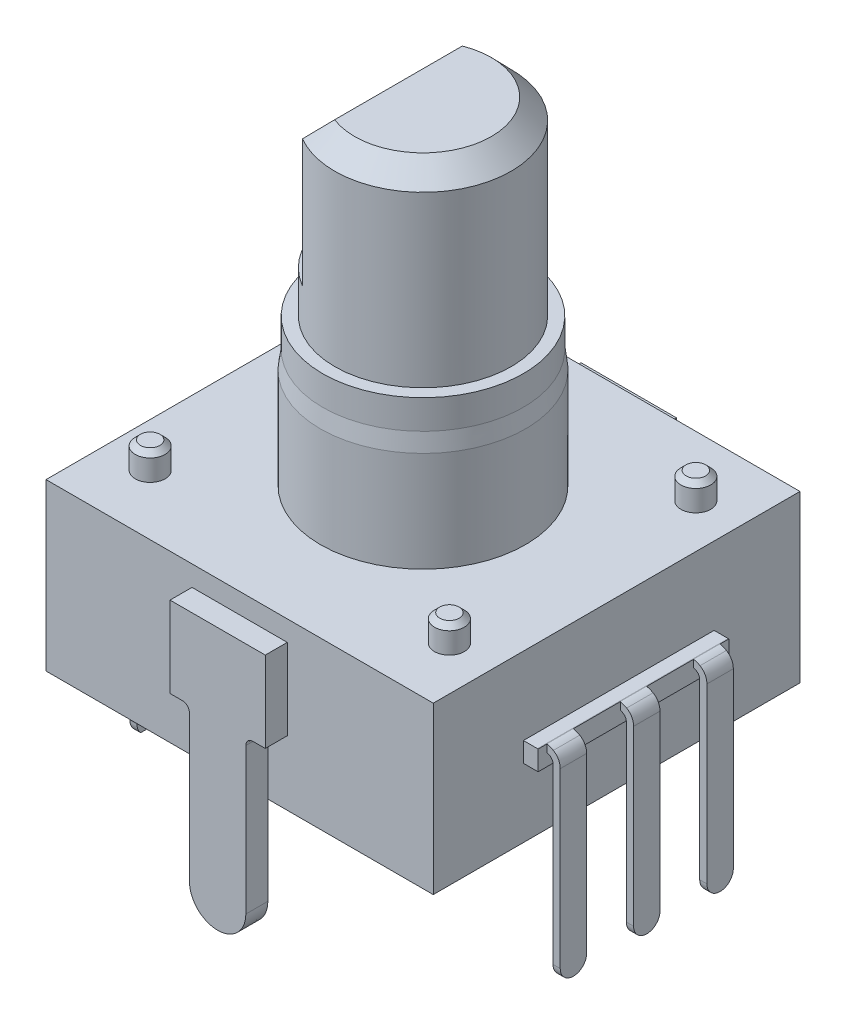
SolidWorks part; units mm, degrees
ref_plane "Front Plane" through (0, 0, 0) normal (0, 0, 1) x (1, 0, 0)
ref_plane "Top Plane" through (0, 0, 0) normal (0, 1, 0) x (1, 0, 0)
ref_plane "Right Plane" through (0, 0, 0) normal (1, 0, 0) x (0, 0, -1)
sketch "Sketch1" plane through (0, 0, 0) normal (0, 0, 1) x (1, 0, 0)
  line L0 (0.9604, -8.6703) -> (0.9604, -3.696)
  line L1 (1.2053, -3.4512) -> (1.6232, -3.4512)
  line L2 (1.6232, -3.4512) -> (1.6232, -2.2855)
  line L3 (1.8681, -2.0407) -> (2.9665, -2.0407)
  line L4 (3.2114, -2.2855) -> (3.2114, -5.6119)
  line L5 (3.2114, -5.6119) -> (4.3519, -5.6119)
  line L6 (4.3519, -5.6119) -> (4.3519, -3.456)
  line L7 (4.5967, -3.211) -> (5.1321, -3.211)
  line L8 (5.1321, -3.211) -> (5.1321, 0)
  line L9 (5.1321, 0) -> (-5.1321, 0)
  line L10 (-5.1321, 0) -> (-5.1321, -3.211)
  line L11 (-5.1321, -3.211) -> (-4.5367, -3.211)
  line L12 (-4.2918, -3.456) -> (-4.2918, -5.6119)
  line L13 (-4.2918, -5.6119) -> (-3.2113, -5.6119)
  line L14 (-3.2113, -5.6119) -> (-3.2113, -2.2855)
  line L15 (-2.9664, -2.0407) -> (-1.868, -2.0407)
  line L16 (-1.623, -2.2855) -> (-1.623, -3.4512)
  line L17 (-1.623, -3.4512) -> (-1.2053, -3.4512)
  line L18 (-0.9604, -3.696) -> (-0.9604, -8.6703)
  line L19 (-4.2918, -5.2036) -> (-4.8159, -5.2036)
  line L20 (-4.8159, -5.2036) -> (-4.8159, -3.211)
  line L21 (4.3519, -5.2036) -> (4.8761, -5.2036)
  line L22 (4.8761, -5.2036) -> (4.8761, -3.211)
  line L23 (-6.5709, -0.3469) -> (-5.132, -0.3469)
  line L24 (-5.132, -0.3469) -> (-5.132, -0.0001)
  line L25 (-5.132, -0.0001) -> (-6.5709, -0.0001)
  line L26 (-6.5709, -0.0001) -> (-6.5709, -0.3469)
  line L27 (-4.8158, -5.0402) -> (-6.5506, -5.0402)
  line L28 (-6.5506, -5.0402) -> (-6.5506, -0.5713)
  line L29 (-6.5506, -0.5713) -> (-5.132, -0.5713)
  line L30 (-6.2444, -5.0402) -> (-6.2444, -5.6524)
  line L31 (-6.2444, -5.6524) -> (-4.7341, -5.6524)
  line L32 (-4.7341, -5.6524) -> (-4.7341, -5.2036)
  line L33 (-5.8974, -0.5713) -> (-5.8974, -0.3468)
  line L34 (-6.4484, -0.5713) -> (-6.4484, -0.3468)
  line L35 (6.6731, -0.3468) -> (5.1321, -0.3468)
  line L36 (5.1321, -0.3468) -> (5.1321, 0)
  line L37 (5.1321, 0) -> (6.6731, 0)
  line L38 (6.6731, 0) -> (6.6731, -0.3468)
  line L39 (5.8976, -0.5713) -> (5.8976, -0.3468)
  line L40 (6.4487, -0.5713) -> (6.4487, -0.3468)
  line L41 (-6.0595, -0.5713) -> (-6.0595, -5.0402)
  line L42 (4.8761, -5.0402) -> (6.6733, -5.0402)
  line L43 (6.6733, -5.0402) -> (6.6733, -0.5713)
  line L44 (6.6733, -0.5713) -> (5.1322, -0.5713)
  line L45 (6.1822, -0.5713) -> (6.1822, -5.0402)
  line L46 (-5.979, -5.6524) -> (-5.979, -5.0402)
  line L47 (-5.7749, -5.6524) -> (-5.7749, -5.0402)
  line L48 (6.123, -5.0402) -> (6.123, -5.6524)
  line L49 (6.123, -5.6524) -> (4.4902, -5.6524)
  line L50 (4.4902, -5.6524) -> (4.4902, -5.2036)
  line L51 (5.8575, -5.6524) -> (5.8575, -5.0402)
  line L52 (5.6534, -5.6524) -> (5.6534, -5.0402)
  line L53 (-3.2112, -5.2239) -> (-0.9603, -5.2239)
  line L54 (0.9605, -5.2239) -> (3.2114, -5.2239)
  line L55 (-1.623, -3.2241) -> (-3.2112, -3.2241)
  line L56 (-3.2112, -2.8161) -> (-1.623, -2.8161)
  line L57 (3.2114, -3.2241) -> (1.6232, -3.2241)
  line L58 (1.6232, -2.8161) -> (3.2114, -2.8161)
  line L59 (7.1438, -2.811) -> (6.6733, -2.811)
  line L60 (6.6733, -2.811) -> (6.6733, -2.5659)
  line L61 (6.6733, -2.5659) -> (7.1532, -2.5659)
  line L62 (7.1532, -2.5659) -> (7.169, -2.5671)
  line L63 (7.6279, -9.4224) -> (7.3829, -9.4224)
  line L64 (7.6276, -3.0711) -> (7.3829, -3.0711)
  line L65 (7.1742, -2.5671) -> (7.1742, -3.2394)
  line L66 (7.1742, -3.2394) -> (6.673, -3.2394)
  line L67 (-6.7103, -4.5472) -> (-6.5507, -4.5472)
  line L68 (-6.5507, -4.5472) -> (-6.5507, -4.792)
  line L69 (-6.5507, -4.792) -> (-6.7234, -4.792)
  line L70 (-6.7234, -4.792) -> (-6.7308, -4.7909)
  line L71 (-6.7308, -4.7909) -> (-6.7314, -4.7913)
  line L72 (-6.7997, -9.2849) -> (-7.0448, -9.2849)
  line L73 (-7.0448, -5.7967) -> (-7.1467, -5.8986)
  line L74 (-7.1467, -5.8986) -> (-7.1467, -8.5227)
  line L75 (-7.1467, -8.5227) -> (-7.0128, -8.6564)
  line L76 (0.9605, -6.6729) -> (-0.9603, -6.6729)
  line L77 (0.9605, -6.8973) -> (-0.9603, -6.8973)
  line L78 (0.9605, -7.4483) -> (-0.9603, -7.4483)
  line L79 (0.9605, -8.1829) -> (-0.9603, -8.1829)
  line L80 (5.1322, -0.6939) -> (-5.132, -0.6939)
  line L81 (4.5922, 0.6938) -> (5.6127, 0.6938)
  line L82 (5.6127, 0.6938) -> (5.6127, -0.0001)
  line L83 (5.6127, -0.0001) -> (4.5922, -0.0001)
  line L84 (4.5922, -0.0001) -> (4.5922, 0.6938)
  line L85 (4.7779, 0.8981) -> (5.4267, 0.8981)
  line L86 (5.4267, 0.8981) -> (5.6125, 0.6938)
  line L87 (5.6125, 0.6938) -> (4.592, 0.6938)
  line L88 (4.592, 0.6938) -> (4.7779, 0.8981)
  line L89 (-5.6249, 0.694) -> (-4.6044, 0.694)
  line L90 (-4.6044, 0.694) -> (-4.6044, 0)
  line L91 (-4.6044, 0) -> (-5.6249, 0)
  line L92 (-5.6249, 0) -> (-5.6249, 0.694)
  line L93 (-5.4391, 0.8981) -> (-4.7903, 0.8981)
  line L94 (-4.7903, 0.8981) -> (-4.6044, 0.6938)
  line L95 (-4.6044, 0.6938) -> (-5.6249, 0.6938)
  line L96 (-5.6249, 0.6938) -> (-5.4391, 0.8981)
  line L97 (3.4953, -0.0002) -> (-3.4842, -0.0002)
  line L98 (-3.4842, -0.0002) -> (-3.4842, 3.4179)
  line L99 (-3.4842, 3.4179) -> (3.4953, 3.4179)
  line L100 (3.4953, 3.4179) -> (3.4953, -0.0002)
  line L101 (3.4188, 4.0148) -> (-3.4076, 4.0148)
  line L102 (-3.4076, 4.0148) -> (-3.4076, 5.0096)
  line L103 (-3.4076, 5.0096) -> (3.4188, 5.0096)
  line L104 (3.4188, 5.0096) -> (3.4953, 3.4179)
  line L105 (3.4953, 3.4179) -> (3.4188, 4.0148)
  line L106 (-3.4842, 3.4179) -> (-3.4076, 4.0148)
  line L107 (-3.1015, 5.9432) -> (3.0056, 5.9432)
  line L108 (3.0056, 5.9432) -> (3.0056, 5.0096)
  line L109 (3.0056, 5.0096) -> (-3.1015, 5.0096)
  line L110 (-3.1015, 5.0096) -> (-3.1015, 5.9432)
  line L111 (-1.5096, 10.7793) -> (-1.5096, 6.4329)
  line L112 (-1.5096, 6.4329) -> (-2.9943, 6.4329)
  line L113 (-2.9943, 6.4329) -> (-2.9943, 5.9432)
  line L114 (-2.9943, 5.9432) -> (3.0056, 5.9432)
  line L115 (3.0056, 5.9432) -> (3.0056, 10.7793)
  line L116 (3.0056, 10.7793) -> (-1.5096, 10.7793)
  line L117 (-0.8362, 11.4681) -> (2.3321, 11.4681)
  line L118 (2.3321, 11.4681) -> (3.0056, 10.7793)
  line L119 (3.0056, 10.7793) -> (-1.5096, 10.7793)
  line L120 (-1.5096, 10.7793) -> (-0.8362, 11.4681)
  spline S0 degree 3 poles (-0.9604, -8.6703) (-0.9604, -9.2007) (-0.5303, -9.6305) (-0.0001, -9.6305) knots 0 0 0 0 1 1 1 1
  spline S1 degree 3 poles (-0.0001, -9.6305) (0.5304, -9.6305) (0.9604, -9.2007) (0.9604, -8.6703) knots 1 1 1 1 2 2 2 2
  spline S2 degree 3 poles (0.9604, -3.696) (0.9604, -3.5613) (1.0706, -3.4512) (1.2053, -3.4512) knots 3 3 3 3 4 4 4 4
  spline S3 degree 3 poles (1.6232, -2.2855) (1.6232, -2.1509) (1.7334, -2.0407) (1.8681, -2.0407) knots 6 6 6 6 7 7 7 7
  spline S4 degree 3 poles (2.9665, -2.0407) (3.1011, -2.0407) (3.2114, -2.1509) (3.2114, -2.2855) knots 8 8 8 8 9 9 9 9
  spline S5 degree 3 poles (4.3519, -3.456) (4.3519, -3.3212) (4.4621, -3.211) (4.5967, -3.211) knots 12 12 12 12 13 13 13 13
  spline S6 degree 3 poles (-4.5367, -3.211) (-4.402, -3.211) (-4.2918, -3.3212) (-4.2918, -3.456) knots 18 18 18 18 19 19 19 19
  spline S7 degree 3 poles (-3.2113, -2.2855) (-3.2113, -2.1509) (-3.101, -2.0407) (-2.9664, -2.0407) knots 22 22 22 22 23 23 23 23
  spline S8 degree 3 poles (-1.868, -2.0407) (-1.7332, -2.0407) (-1.623, -2.1509) (-1.623, -2.2855) knots 24 24 24 24 25 25 25 25
  spline S9 degree 3 poles (-1.2053, -3.4512) (-1.0706, -3.4512) (-0.9604, -3.5613) (-0.9604, -3.696) knots 27 27 27 27 28 28 28 28
  spline S10 degree 3 poles (7.3829, -9.4224) (7.3827, -9.4224) (7.3827, -3.4078) (7.3829, -3.0711) knots 0 0 0 0 1 1 1 1
  spline S11 degree 3 poles (7.3829, -3.0711) (7.3829, -2.8966) (7.2574, -2.8477) (7.1742, -2.8184) knots 1 1 1 1 2 2 2 2
  spline S12 degree 3 poles (7.1742, -2.8184) (7.1597, -2.8143) (7.1496, -2.8121) (7.1438, -2.811) knots 2 2 2 2 3 3 3 3
  spline S13 degree 3 poles (7.169, -2.5671) (7.1784, -2.5688) (7.2801, -2.5812) (7.3928, -2.6489) knots 7 7 7 7 8 8 8 8
  spline S14 degree 3 poles (7.3928, -2.6489) (7.505, -2.7135) (7.6302, -2.8568) (7.6276, -3.0711) knots 8 8 8 8 9 9 9 9
  spline S15 degree 3 poles (7.6276, -3.0711) (7.6276, -3.4076) (7.6276, -9.4224) (7.6279, -9.4224) knots 9 9 9 9 10 10 10 10
  spline S16 degree 3 poles (-7.0448, -9.2849) (-7.0448, -9.2847) (-7.0448, -5.1254) (-7.0448, -4.8849) knots 0 0 0 0 1 1 1 1
  spline S17 degree 3 poles (-7.0448, -4.8849) (-7.0474, -4.7576) (-6.9914, -4.6523) (-6.9154, -4.6021) knots 1 1 1 1 2 2 2 2
  spline S18 degree 3 poles (-6.9154, -4.6021) (-6.8412, -4.5511) (-6.7694, -4.547) (-6.7314, -4.5465) knots 2 2 2 2 3 3 3 3
  spline S19 degree 3 poles (-6.7314, -4.5465) (-6.7228, -4.5465) (-6.7158, -4.5469) (-6.7103, -4.5472) knots 3 3 3 3 4 4 4 4
  spline S20 degree 3 poles (-6.7314, -4.7913) (-6.7426, -4.7906) (-6.7661, -4.7952) (-6.775, -4.8023) knots 9 9 9 9 10 10 10 10
  spline S21 degree 3 poles (-6.775, -4.8023) (-6.7823, -4.8103) (-6.7973, -4.8132) (-6.7999, -4.8849) knots 10 10 10 10 11 11 11 11
  spline S22 degree 3 poles (-6.7999, -4.8849) (-6.7999, -5.1254) (-6.7999, -9.2805) (-6.7997, -9.2849) knots 11 11 11 11 12 12 12 12
sketch "Sketch2" plane through (0, 0, 0) normal (0, 0, 1) x (1, 0, 0)
  line L0 (0, 0) -> (0, -13.1499) construction
  line L1 (0, -13.5399) -> (0, 13.5399) construction
  line L2 (-0.8362, 11.4681) -> (2.3321, 11.4681) construction
  line L3 (2.3321, 11.4681) -> (3.0056, 10.7793) construction
  line L4 (3.0056, 5.9432) -> (3.0056, 10.7793) construction
  line L5 (0, 11.4681) -> (0, 0)
  line L7 (-3.4842, 3.4179) -> (3.4953, 3.4179) construction
  line L8 (3.4953, 3.4179) -> (3.4953, -0.0002) construction
  line L10 (0, 11.4681) -> (2.3321, 11.4681)
  line L11 (2.3321, 11.4681) -> (3.0056, 10.7793)
  line L12 (3.0056, 5.0096) -> (3.0056, 10.7793)
  line L14 (3.0056, 5.0096) -> (3.4188, 5.0096)
  line L15 (3.4188, 5.0096) -> (3.4188, 4.0148)
  line L16 (3.4953, 3.4179) -> (3.4953, 0)
  line L18 (3.4188, 4.0148) -> (3.4953, 3.4179)
  line L19 (-3.4076, 5.0096) -> (3.4188, 5.0096) construction
  line L20 (3.4953, 0) -> (0, 0)
revolve "Revolve10" add sketch "Sketch2" angle 360 about L0
sketch "Sketch3" plane through (0, 0, 0) normal (0, 0, 1) x (1, 0, 0)
  line L0 (-1.5096, 6.4329) -> (-2.9943, 6.4329) construction
  line L1 (-1.5096, 10.7793) -> (-1.5096, 6.4329) construction
  line L2 (-1.5096, 6.4329) -> (-3.0056, 6.4329)
  line L3 (-1.5096, 11.4681) -> (-1.5096, 6.4329)
  line L4 (-3.0056, 10.7793) -> (-3.0056, 5.0096) construction
  line L5 (2.3321, 11.4681) -> (-2.3321, 11.4681) construction
  line L6 (-3.0056, 11.4681) -> (-3.0056, 6.4329)
  line L7 (-1.5096, 11.4681) -> (-3.0056, 11.4681)
extrude "Cut-Extrude1" cut sketch "Sketch3" against normal up to next and the other way up to next
sketch "Sketch4" plane through (0, 0, 0) normal (0, -1, 0) x (1, 0, 0)
  line L1 (-6.6, -6.25) -> (6.6, -6.25)
  line L2 (-6.6, -6.25) -> (-6.6, 6.25)
  line L3 (-6.6, 6.25) -> (6.6, 6.25)
  line L4 (6.6, -6.25) -> (6.6, 6.25)
  line L5 (-6.6, -6.25) -> (6.6, 6.25) construction
  line L6 (-6.6, 6.25) -> (6.6, -6.25) construction
  point P0 (0, 0)
  dimension "D1" = 13.2
  dimension "D2" = 12.5
extrude "Boss-Extrude1" add sketch "Sketch4" along normal up to vertex (5.6524 mm away) up to point (-4.7341, -5.6524, 0)
sketch "Sketch5" plane through (0, 0, 0) normal (0, 0, 1) x (1, 0, 0)
  line L0 (-1.5096, 10.7793) -> (-0.8362, 11.4681) construction
  line L1 (-1.5096, 10.7793) -> (-0.8362, 11.4681)
  line L2 (-1.5096, 10.7793) -> (-1.5096, 11.4681)
  line L3 (-1.5096, 11.4681) -> (-0.8362, 11.4681)
extrude "Cut-Extrude2" cut sketch "Sketch5" against normal up to next and the other way up to next
sketch "Sketch6" plane through (0, 0, 0) normal (0, 1, 0) x (1, 0, 0)
  line L0 (0, 0) -> (0, 8.5463) construction
  line L1 (0, -6.875) -> (0, 6.875) construction
  line L2 (0, 0) -> (11.4741, 0) construction
  circle A0 centre (-5.1, 4.2) radius 0.508
  circle A1 centre (5.1, 4.2) radius 0.508
  circle A2 centre (5.1, -4.2) radius 0.508
  circle A3 centre (-5.1, -4.2) radius 0.508
  dimension "D1" = 8.4
  dimension "D2" = 10.2
  dimension "D3" = 1.016
extrude "Boss-Extrude2" add sketch "Sketch6" along normal up to vertex (0.8981 mm away) up to point (-4.7903, 0.8981, 0)
chamfer "Chamfer1" distance 0.1778 angle 45 4 edges at (5.1, 0.8981, -3.692) (5.1, 0.8981, 4.708) (-5.1, 0.8981, -3.692) (-5.1, 0.8981, 4.708)
sketch "Sketch7" plane through (0, 0, 6.25) normal (0, 0, 1) x (1, 0, 0)
  line L0 (-1.623, -2.2855) -> (-1.623, -3.4512) construction
  line L1 (-1.623, -3.4512) -> (-1.2053, -3.4512) construction
  line L2 (-0.9604, -3.696) -> (-0.9604, -8.6703) construction
  line L3 (0.9604, -8.6703) -> (0.9604, -3.696) construction
  line L4 (1.2053, -3.4512) -> (1.6232, -3.4512) construction
  line L5 (1.6232, -3.4512) -> (1.6232, -2.2855) construction
  line L6 (5.1322, -0.6939) -> (-5.132, -0.6939) construction
  line L7 (-1.623, -0.6939) -> (-1.623, -3.4512)
  line L8 (-1.623, -3.4512) -> (-1.2053, -3.4512)
  line L9 (-0.9604, -3.696) -> (-0.9604, -8.6703)
  line L10 (0.9604, -8.6703) -> (0.9604, -3.696)
  line L11 (1.2053, -3.4512) -> (1.6232, -3.4512)
  line L12 (1.6232, -3.4512) -> (1.6232, -0.6939)
  line L13 (1.6232, -0.6939) -> (-1.623, -0.6939)
  spline S0 degree 3 poles (1943.8592, -2286.133) (-2070.6571, 2174.6987) (2182.9501, -2067.0268) (-2288.9997, 1934.9357) knots -1.659555 -1.659555 -1.659555 -1.659555 56.657088 56.657088 56.657088 56.657088 only from (-1.2053, -3.4512) to (-0.9604, -3.696) construction
  spline S1 degree 3 poles (2377.6186, -1832.4346) (-2221.6581, 2023.1897) (2037.0941, -2225.5259) (-1829.3523, 2364.642) knots -18.097303 -18.097303 -18.097303 -18.097303 19.098909 19.098909 19.098909 19.098909 only from (-0.9604, -8.6703) to (-0.0001, -9.6305) construction
  spline S2 degree 3 poles (1827.1972, 2366.3822) (-2035.2287, -2227.2818) (2220.0923, 2024.9396) (-2376.3586, -1834.1534) knots -17.103608 -17.103608 -17.103608 -17.103608 20.102828 20.102828 20.102828 20.102828 only from (-0.0001, -9.6305) to (0.9604, -8.6703) construction
  spline S3 degree 3 poles (2289.0612, 1934.9907) (-2182.9667, -2067.0457) (2070.6329, 2174.6767) (-1943.799, -2286.0661) knots -25.657355 -25.657355 -25.657355 -25.657355 32.659263 32.659263 32.659263 32.659263 only from (0.9604, -3.696) to (1.2053, -3.4512) construction
  spline S4 degree 3 poles (-1.2053, -3.4512) (-1.0706, -3.4512) (-0.9604, -3.5613) (-0.9604, -3.696) knots 27 27 27 27 28 28 28 28
  spline S5 degree 3 poles (-0.9604, -8.6703) (-0.9604, -9.2007) (-0.5303, -9.6305) (-0.0001, -9.6305) knots 0 0 0 0 1 1 1 1
  spline S6 degree 3 poles (-0.0001, -9.6305) (0.5304, -9.6305) (0.9604, -9.2007) (0.9604, -8.6703) knots 1 1 1 1 2 2 2 2
  spline S7 degree 3 poles (0.9604, -3.696) (0.9604, -3.5613) (1.0706, -3.4512) (1.2053, -3.4512) knots 3 3 3 3 4 4 4 4
extrude "Boss-Extrude3" add sketch "Sketch7" along normal offset from surface (0.75 mm away) 7 up to plane "Front Plane"
sketch "Sketch8" plane through (0, 0, -6.25) normal (0, 0, -1) x (-1, 0, 0)
  line L7 (1.623, -0.6939) -> (1.623, -3.4512) construction
  line L8 (-1.6232, -0.6939) -> (1.623, -0.6939) construction
  line L9 (-1.6232, -3.4512) -> (-1.6232, -0.6939) construction
  line L10 (-1.2053, -3.4512) -> (-1.6232, -3.4512) construction
  line L11 (-0.9604, -8.6703) -> (-0.9604, -3.696) construction
  line L12 (1.623, -3.4512) -> (1.2053, -3.4512) construction
  line L13 (0.9604, -3.696) -> (0.9604, -8.6703) construction
  line L14 (1.623, -0.6939) -> (1.623, -3.4512)
  line L15 (-1.6232, -0.6939) -> (1.623, -0.6939)
  line L16 (-1.6232, -3.4512) -> (-1.6232, -0.6939)
  line L17 (-1.2053, -3.4512) -> (-1.6232, -3.4512)
  line L18 (-0.9604, -8.6703) -> (-0.9604, -3.696)
  line L19 (1.623, -3.4512) -> (1.2053, -3.4512)
  line L20 (0.9604, -3.696) -> (0.9604, -8.6703)
  spline S4 degree 3 poles (-2289.0612, 1934.9907) (2182.9667, -2067.0457) (-2070.6329, 2174.6767) (1943.799, -2286.0661) knots -25.657355 -25.657355 -25.657355 -25.657355 32.659263 32.659263 32.659263 32.659263 only from (-0.9604, -3.696) to (-1.2053, -3.4512) construction
  spline S5 degree 3 poles (-1943.8592, -2286.133) (2070.6571, 2174.6987) (-2182.9501, -2067.0268) (2288.9997, 1934.9357) knots -1.659555 -1.659555 -1.659555 -1.659555 56.657088 56.657088 56.657088 56.657088 only from (1.2053, -3.4512) to (0.9604, -3.696) construction
  spline S6 degree 3 poles (-1827.1972, 2366.3822) (2035.2287, -2227.2818) (-2220.0923, 2024.9396) (2376.3586, -1834.1534) knots -17.103608 -17.103608 -17.103608 -17.103608 20.102828 20.102828 20.102828 20.102828 only from (0.0001, -9.6305) to (-0.9604, -8.6703) construction
  spline S7 degree 3 poles (-2377.6186, -1832.4346) (2221.6581, 2023.1897) (-2037.0941, -2225.5259) (1829.3523, 2364.642) knots -18.097303 -18.097303 -18.097303 -18.097303 19.098909 19.098909 19.098909 19.098909 only from (0.9604, -8.6703) to (0.0001, -9.6305) construction
  spline S8 degree 3 poles (-0.9604, -3.696) (-0.9604, -3.5613) (-1.0706, -3.4512) (-1.2053, -3.4512) knots 3 3 3 3 4 4 4 4
  spline S9 degree 3 poles (1.2053, -3.4512) (1.0706, -3.4512) (0.9604, -3.5613) (0.9604, -3.696) knots 27 27 27 27 28 28 28 28
  spline S10 degree 3 poles (0.0001, -9.6305) (-0.5304, -9.6305) (-0.9604, -9.2007) (-0.9604, -8.6703) knots 1 1 1 1 2 2 2 2
  spline S11 degree 3 poles (0.9604, -8.6703) (0.9604, -9.2007) (0.5303, -9.6305) (0.0001, -9.6305) knots 0 0 0 0 1 1 1 1
extrude "Boss-Extrude6" add sketch "Sketch8" along normal blind 0.762
sketch "Sketch9" plane through (0, 0, 0) normal (0, 0, 1) x (1, 0, 0)
  line L0 (7.6279, -9.4224) -> (7.3829, -9.4224) construction
  line L1 (7.1438, -2.811) -> (6.6733, -2.811) construction
  line L2 (6.6733, -2.5659) -> (7.1532, -2.5659) construction
  line L3 (7.6279, -9.4224) -> (7.3829, -9.4224)
  line L4 (7.1438, -2.811) -> (6.6733, -2.811)
  line L5 (6.6733, -2.5659) -> (7.1532, -2.5659)
  line L6 (6.6733, -2.5659) -> (6.6733, -2.811)
  line L7 (7.1532, -2.5659) -> (7.169, -2.5671) construction
  line L8 (7.1532, -2.5659) -> (7.169, -2.5671)
  spline S0 degree 3 poles (7.4119, 2990.4518) (7.3729, -3082.06) (7.373, 3069.5853) (7.4122, -3002.9425) knots -5.87931 -5.87931 -5.87931 -5.87931 6.908121 6.908121 6.908121 6.908121 only from (7.3829, -9.4224) to (7.3829, -3.0711) construction
  spline S1 degree 3 poles (7.5536, -3002.9665) (7.7137, 3069.6073) (7.5273, -3082.0798) (7.7444, 2990.4696) knots 3.092004 3.092004 3.092004 3.092004 15.879203 15.879203 15.879203 15.879203 only from (7.6276, -3.0711) to (7.6279, -9.4224) construction
  spline S2 degree 3 poles (-2486.0026, -1670.96) (2535.0932, 1621.3335) (-2546.3243, -1586.5894) (2577.3565, 1544.0817) knots -22.859776 -22.859776 -22.859776 -22.859776 26.605734 26.605734 26.605734 26.605734 only from (7.3829, -3.0711) to (7.1742, -2.8184) construction
  spline S3 degree 3 poles (2706.2023, 1306.1502) (-2651.9945, -1400.7258) (2613.6091, 1491.0522) (-2532.39, -1598.0634) knots -24.066068 -24.066068 -24.066068 -24.066068 39.696984 39.696984 39.696984 39.696984 only from (7.169, -2.5671) to (7.3928, -2.6489) construction
  spline S4 degree 3 poles (2988.1123, -336.8588) (-2991.9303, 221.2699) (3012.9217, -107.1244) (-2991.6166, -26.9825) knots -19.606972 -19.606972 -19.606972 -19.606972 35.848031 35.848031 35.848031 35.848031 only from (7.3928, -2.6489) to (7.6276, -3.0711) construction
  spline S5 degree 3 poles (7.3829, -9.4224) (7.3827, -9.4224) (7.3827, -3.4078) (7.3829, -3.0711) knots 0 0 0 0 1 1 1 1
  spline S6 degree 3 poles (7.6276, -3.0711) (7.6276, -3.4076) (7.6276, -9.4224) (7.6279, -9.4224) knots 9 9 9 9 10 10 10 10
  spline S7 degree 3 poles (7.3829, -3.0711) (7.3829, -2.8966) (7.2574, -2.8477) (7.1742, -2.8184) knots 1 1 1 1 2 2 2 2
  spline S8 degree 3 poles (7.169, -2.5671) (7.1784, -2.5688) (7.2801, -2.5812) (7.3928, -2.6489) knots 7 7 7 7 8 8 8 8
  spline S9 degree 3 poles (7.3928, -2.6489) (7.505, -2.7135) (7.6302, -2.8568) (7.6276, -3.0711) knots 8 8 8 8 9 9 9 9
  spline S10 degree 3 poles (1067.2242, -2808.1605) (-897.7386, 2848.1596) (748.7669, -2899.9904) (-562.9129, 2941.1766) knots -145.362266 -145.362266 -145.362266 -145.362266 156.359232 156.359232 156.359232 156.359232 only from (7.1742, -2.8184) to (7.1438, -2.811) construction
  spline S11 degree 3 poles (7.1742, -2.8184) (7.1597, -2.8143) (7.1496, -2.8121) (7.1438, -2.811) knots 2 2 2 2 3 3 3 3
extrude "Boss-Extrude7" add sketch "Sketch9" along normal mid plane 0.9 separate body
pattern_linear "LPattern1" count 2 spacing 2.5 along (0, 0, 1) of "Boss-Extrude7"
pattern_linear "LPattern2" count 2 spacing 2.5 along (0, 0, 1) of "Boss-Extrude7"
sketch "Sketch10" plane through (0, 0, 0) normal (0, 0, 1) x (1, 0, 0)
  line L0 (7.1742, -3.2394) -> (6.673, -3.2394) construction
  line L1 (7.1742, -2.5671) -> (7.1742, -3.2394) construction
  line L2 (6.6733, -2.5659) -> (7.1532, -2.5659) construction
  line L3 (6.6733, -5.0402) -> (6.6733, -0.5713) construction
  line L4 (7.1742, -3.2394) -> (6.6733, -3.2394)
  line L5 (7.1742, -2.5679) -> (7.1742, -3.2394)
  line L6 (6.6733, -2.5659) -> (7.1532, -2.5659)
  line L7 (6.6733, -3.2394) -> (6.6733, -2.5659)
  line L8 (7.1532, -2.5659) -> (7.169, -2.5671) construction
  line L9 (7.1532, -2.5659) -> (7.169, -2.5671)
  spline S0 degree 3 poles (2706.2023, 1306.1502) (-2651.9945, -1400.7258) (2613.6091, 1491.0522) (-2532.39, -1598.0634) knots -24.066068 -24.066068 -24.066068 -24.066068 39.696984 39.696984 39.696984 39.696984 only from (7.169, -2.5671) to (7.3928, -2.6489) construction
  spline S1 degree 3 poles (7.169, -2.5671) (7.1699, -2.5672) (7.1716, -2.5675) (7.1742, -2.5679) knots 7 7 7 7 7.095488 7.095488 7.095488 7.095488
extrude "Boss-Extrude8" add sketch "Sketch10" along normal mid plane 6.5
sketch "Sketch11" plane through (0, 0, 0) normal (0, 0, 1) x (1, 0, 0)
  line L0 (-6.5507, -4.792) -> (-6.7234, -4.792) construction
  line L1 (-6.7103, -4.5472) -> (-6.5507, -4.5472) construction
  line L2 (-6.7997, -9.2849) -> (-7.0448, -9.2849) construction
  line L3 (-6.5507, -4.792) -> (-6.7439, -4.792)
  line L4 (-6.7103, -4.5472) -> (-6.5507, -4.5472)
  line L5 (-6.7997, -9.2849) -> (-7.0448, -9.2849)
  line L6 (-6.5507, -4.5472) -> (-6.5507, -4.792)
  arc A0 (-6.7103, -4.5472) -> (-6.7314, -4.5465) centre (-6.7316, -4.8635) ccw construction
  arc A1 (-6.7103, -4.5472) -> (-6.7314, -4.5465) centre (-6.7316, -4.8635) ccw
  spline S0 degree 3 poles (-2989.7977, -321.8047) (2981.3004, 294.7219) (-2996.5858, -286.1077) (2981.6322, 257.6135) knots -38.486589 -38.486589 -38.486589 -38.486589 57.43348 57.43348 57.43348 57.43348 only from (-6.7314, -4.7913) to (-6.775, -4.8023) construction
  spline S1 degree 3 poles (-822.7708, 2882.0363) (796.5324, -2894.3842) (-796.2504, 2888.5533) (767.7076, -2902.9787) knots -23.867815 -23.867815 -23.867815 -23.867815 44.048212 44.048212 44.048212 44.048212 only from (-6.775, -4.8023) to (-6.7999, -4.8849) construction
  spline S2 degree 3 poles (1643.5881, -2509.2813) (-1735.9046, 2448.3974) (1792.507, -2406.7961) (-1867.6071, 2348.0819) knots -35.628125 -35.628125 -35.628125 -35.628125 40.997034 40.997034 40.997034 40.997034 only from (-6.9154, -4.6021) to (-6.7314, -4.5465) construction
  spline S3 degree 3 poles (2425.4394, 1748.8576) (-2339.378, -1898.8313) (2217.0023, 2016.1073) (-2114.2753, -2138.1902) knots -37.37918 -37.37918 -37.37918 -37.37918 40.568404 40.568404 40.568404 40.568404 only from (-7.0448, -4.8849) to (-6.9154, -4.6021) construction
  spline S4 degree 3 poles (-6.8732, -3004.7896) (-6.7161, 3052.4838) (-6.8958, -3066.6195) (-6.6902, 2990.562) knots 4.258592 4.258592 4.258592 4.258592 18.712092 18.712092 18.712092 18.712092 only from (-6.7999, -4.8849) to (-6.7997, -9.2849) construction
  spline S5 degree 3 poles (-7.0448, 2990.6113) (-7.0448, -3066.6438) (-7.0448, 3052.4824) (-7.0448, -3004.7634) knots -6.708148 -6.708148 -6.708148 -6.708148 7.737877 7.737877 7.737877 7.737877 only from (-7.0448, -9.2849) to (-7.0448, -4.8849) construction
  spline S6 degree 3 poles (-6.7439, -4.792) (-6.7552, -4.7936) (-6.7688, -4.7973) (-6.775, -4.8023) knots 9.296376 9.296376 9.296376 9.296376 10 10 10 10
  spline S7 degree 3 poles (-6.775, -4.8023) (-6.7823, -4.8103) (-6.7973, -4.8132) (-6.7999, -4.8849) knots 10 10 10 10 11 11 11 11
  spline S8 degree 3 poles (-6.9154, -4.6021) (-6.8412, -4.5511) (-6.7694, -4.547) (-6.7314, -4.5465) knots 2 2 2 2 3 3 3 3
  spline S9 degree 3 poles (-7.0448, -4.8849) (-7.0474, -4.7576) (-6.9914, -4.6523) (-6.9154, -4.6021) knots 1 1 1 1 2 2 2 2
  spline S10 degree 3 poles (-6.7999, -4.8849) (-6.7999, -5.1254) (-6.7999, -9.2805) (-6.7997, -9.2849) knots 11 11 11 11 12 12 12 12
  spline S11 degree 3 poles (-7.0448, -9.2849) (-7.0448, -9.2847) (-7.0448, -5.1254) (-7.0448, -4.8849) knots 0 0 0 0 1 1 1 1
extrude "Boss-Extrude9" add sketch "Sketch11" along normal mid plane 0.9 from offset 2.5
pattern_linear "LPattern3" count 2 spacing 5 along (0, 0, -1) of "Boss-Extrude9"
sketch "Sketch12" plane through (0, 0, 0) normal (1, 0, 0) x (0, 0, -1)
  line L0 (-2.95, -3.0711) -> (-2.95, -9.4224) construction
  line L1 (-2.05, -9.4224) -> (-2.05, -3.0711) construction
  line L2 (-0.45, -3.0711) -> (-0.45, -9.4224) construction
  line L3 (0.45, -9.4224) -> (0.45, -3.0711) construction
  line L4 (2.05, -3.0711) -> (2.05, -9.4224) construction
  line L5 (2.95, -9.4224) -> (2.95, -3.0711) construction
  line L6 (-2.95, -9.4224) -> (-2.05, -9.4224) construction
  line L7 (-0.45, -9.4224) -> (0.45, -9.4224) construction
  line L8 (2.05, -9.4224) -> (2.95, -9.4224) construction
  line L9 (-2.95, -8.9724) -> (-2.95, -9.5494)
  line L10 (-2.95, -9.5494) -> (-2.05, -9.5494)
  line L11 (-2.05, -9.5494) -> (-2.05, -8.9724)
  line L12 (-0.45, -8.9724) -> (-0.45, -9.5494)
  line L13 (-0.45, -9.5494) -> (0.45, -9.5494)
  line L14 (0.45, -9.5494) -> (0.45, -8.9724)
  line L15 (2.05, -8.9724) -> (2.05, -9.5494)
  line L16 (2.05, -9.5494) -> (2.95, -9.5494)
  line L17 (2.95, -9.5494) -> (2.95, -8.9724)
  arc A0 (-2.95, -8.9724) -> (-2.05, -8.9724) centre (-2.5, -8.9724) ccw
  arc A1 (-0.45, -8.9724) -> (0.45, -8.9724) centre (0, -8.9724) ccw
  arc A2 (2.05, -8.9724) -> (2.95, -8.9724) centre (2.5, -8.9724) ccw
  dimension "D1" = 0.127
extrude "Cut-Extrude5" cut sketch "Sketch12" against normal blind 7.366 and the other way blind 9.525
